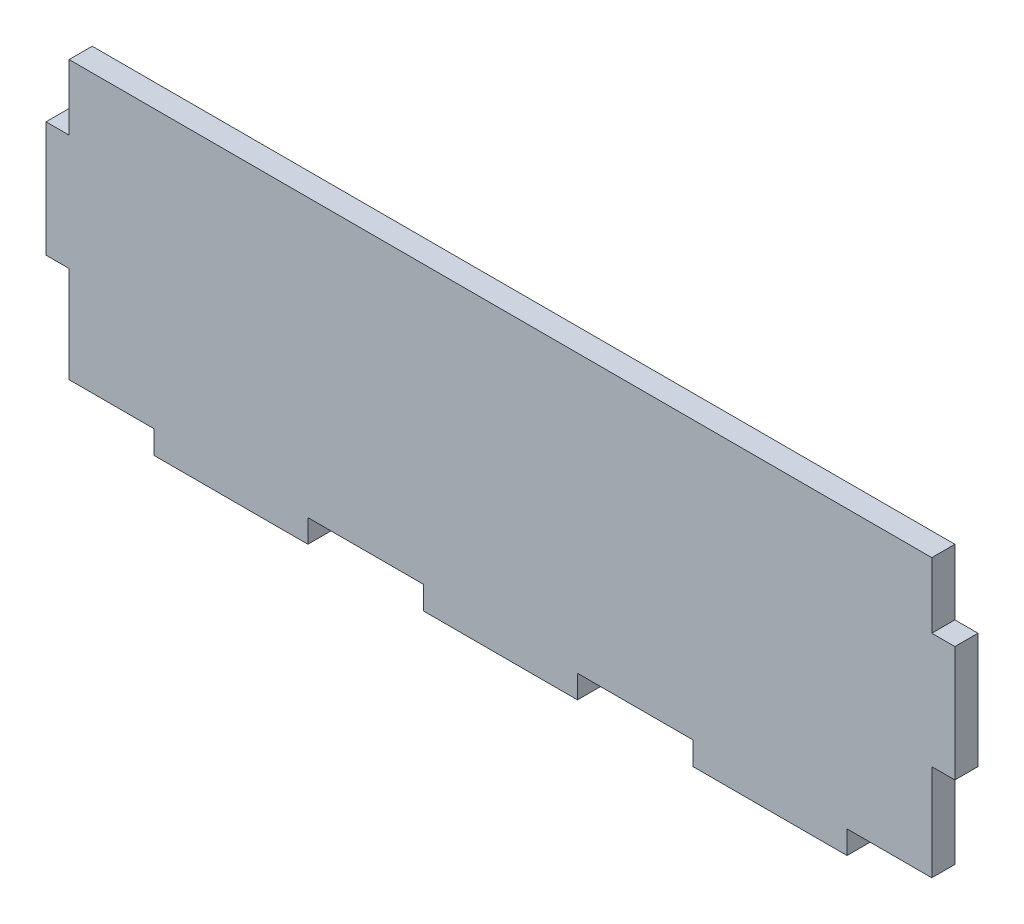
SolidWorks part; units mm, degrees
ref_plane "Front Plane" through (0, 0, 0) normal (0, 0, 1) x (1, 0, 0)
ref_plane "Top Plane" through (0, 0, 0) normal (0, 1, 0) x (1, 0, 0)
ref_plane "Right Plane" through (0, 0, 0) normal (1, 0, 0) x (0, 0, -1)
sketch "Sketch1" plane through (0, 0, 0) normal (0, 0, 1) x (1, 0, 0)
  line L0 (0, -55) -> (0, 55) construction
  line L1 (56, -20) -> (-56, -20)
  line L2 (56, -20) -> (56, 20)
  line L3 (56, 20) -> (-56, 20)
  line L4 (-56, -20) -> (-56, 20)
  line L5 (56, -20) -> (-56, 20) construction
  line L6 (56, 20) -> (-56, -20) construction
  line L7 (-59, 7.5) -> (-56, 7.5)
  line L8 (-59, 7.5) -> (-59, -7.5)
  line L9 (-59, -7.5) -> (-56, -7.5)
  line L10 (-56, 7.5) -> (-56, -7.5)
  line L11 (-59, 7.5) -> (-56, -7.5) construction
  line L12 (-59, -7.5) -> (-56, 7.5) construction
  line L13 (59, -7.5) -> (56, -7.5)
  line L14 (56, 7.5) -> (56, -7.5)
  line L15 (59, 7.5) -> (56, 7.5)
  line L16 (59, 7.5) -> (59, -7.5)
  line L17 (45, -20) -> (25, -20)
  line L18 (-10, -23) -> (10, -23)
  line L19 (-10, -23) -> (-10, -20)
  line L20 (-10, -20) -> (10, -20)
  line L21 (10, -23) -> (10, -20)
  line L22 (-10, -23) -> (10, -20) construction
  line L23 (-10, -20) -> (10, -23) construction
  line L24 (-45, -23) -> (-25, -23)
  line L25 (-45, -23) -> (-45, -20)
  line L26 (-45, -20) -> (-25, -20)
  line L27 (-25, -23) -> (-25, -20)
  line L28 (-45, -23) -> (-25, -20) construction
  line L29 (-45, -20) -> (-25, -23) construction
  line L30 (25, -23) -> (25, -20)
  line L31 (45, -23) -> (25, -23)
  line L32 (45, -23) -> (45, -20)
  point P0 (0, 0)
  point P6 (-57.5, 0)
  point P11 (-35, -21.5)
  point P18 (0, -21.5)
  point P27 (0, 0)
  dimension "D1" = 112
  dimension "D2" = 40
  dimension "D3" = 3
  dimension "D4" = 15
  dimension "D5" = 3
  dimension "D6" = 20
  dimension "D7" = 15
extrude "Boss-Extrude1" add sketch "Sketch1" along normal blind 3 contours L8 L9 L4 L7 | L4 L1 L2 L3 | L24 L27 L1 L25 | L18 L21 L1 L19 | L31 L32 L1 L30 | L16 L15 L2 L13
sketch "Sketch2" plane through (0, 0, 3) normal (0, 0, 1) x (1, 0, 0)
  line L0 (56, 7.5) -> (56, 20) construction
  line L1 (-56, 20) -> (56, 20)
  line L2 (-56, 20) -> (-56, 16)
  line L3 (-56, 16) -> (56, 16)
  line L4 (56, 20) -> (56, 16)
  dimension "D1" = 4
extrude "Cut-Extrude1" cut sketch "Sketch2" against normal blind 3
